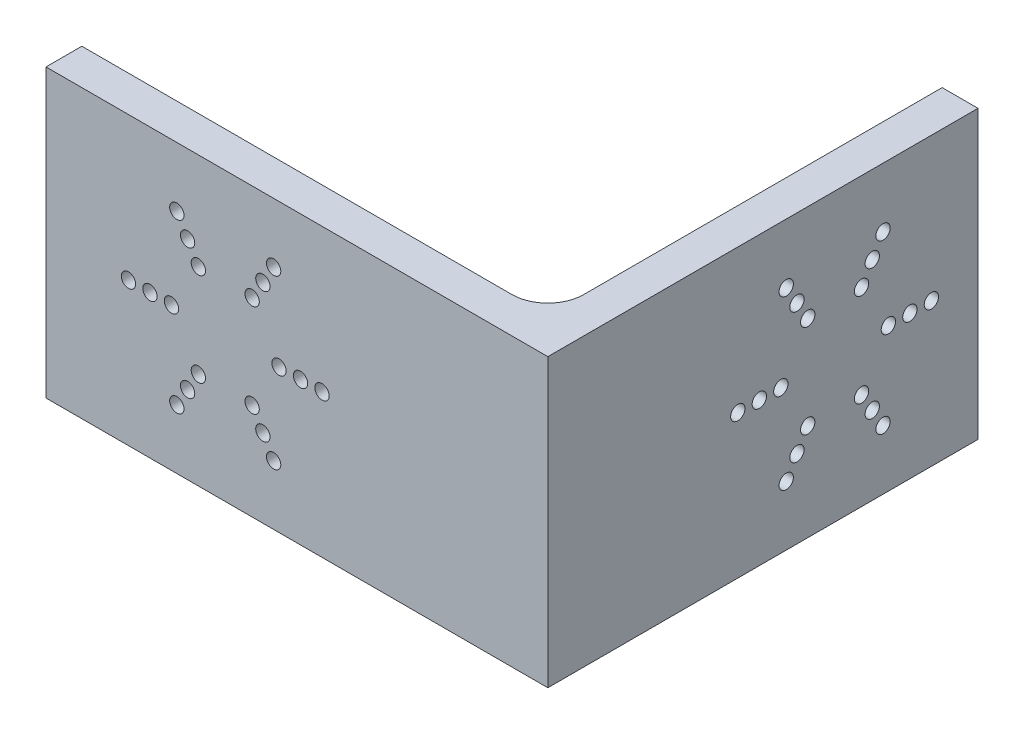
SolidWorks part; units mm, degrees
material "Polylactic Acid"
ref_plane "Top Plane" through (0, 0, 0) normal (0, 0, 1) x (1, 0, 0)
ref_plane "Right Plane" through (0, 0, 0) normal (0, 1, 0) x (1, 0, 0)
ref_plane "Front Plane" through (0, 0, 0) normal (1, 0, 0) x (0, 0, -1)
sketch "Sketch1" plane through (0, 0, 0) normal (0, 1, 0) x (1, 0, 0)
  line L1 (35, -30) -> (-35, -30)
  line L2 (35, -30) -> (35, 30)
  line L3 (35, 30) -> (-35, 30)
  line L4 (-35, -30) -> (-35, 30)
  line L5 (35, -30) -> (-35, 30) construction
  line L6 (35, 30) -> (-35, -30) construction
  point P0 (0, 0)
  dimension "D1" = 70
  dimension "D2" = 60
extrude "Boss-Extrude1" add sketch "Sketch1" along normal mid plane 40
sketch "Sketch2" plane through (0, 20, 0) normal (0, 1, 0) x (1, 0, 0)
  line L0 (-35, -30) -> (35, -30) construction
  line L1 (-35, 30) -> (30, 30)
  line L2 (-35, 30) -> (-35, -25)
  line L3 (-35, -25) -> (30, -25)
  line L4 (30, 30) -> (30, -25)
  line L5 (35, -30) -> (35, 30) construction
  dimension "D1" = 5
  dimension "D2" = 5
extrude "Cut-Extrude1" cut sketch "Sketch2" against normal up to surface (40 mm away) up to face at (0, -20, 0)
fillet "Fillet1" radius 5 1 edges at (30, 0, 25)
sketch "Sketch3" plane through (0, 0, 30) normal (0, 0, 1) x (1, 0, 0)
  line L0 (-2.5, 0) -> (0.5, 0) construction
  line L1 (-6.25, -6.4952) -> (-4.75, -9.0933) construction
  line L11 (-13.75, -6.4952) -> (-15.25, -9.0933) construction
  line L12 (-17.5, 0) -> (-20.5, 0) construction
  line L13 (-13.75, 6.4952) -> (-15.25, 9.0933) construction
  line L14 (-6.25, 6.4952) -> (-4.75, 9.0933) construction
  line L15 (-10, 0) -> (-2.5, 0) construction
  line L19 (-35, 20) -> (-35, -20) construction
  circle A4 centre (-2.5, 0) radius 1
  circle A5 centre (0.5, 0) radius 1
  circle A6 centre (3.5, 0) radius 1
  circle A7 centre (-6.25, -6.4952) radius 1
  circle A8 centre (-4.75, -9.0933) radius 1
  circle A9 centre (-3.25, -11.6913) radius 1
  circle A10 centre (-13.75, -6.4952) radius 1
  circle A11 centre (-15.25, -9.0933) radius 1
  circle A12 centre (-16.75, -11.6913) radius 1
  circle A13 centre (-17.5, 0) radius 1
  circle A14 centre (-20.5, 0) radius 1
  circle A15 centre (-23.5, 0) radius 1
  circle A16 centre (-13.75, 6.4952) radius 1
  circle A17 centre (-15.25, 9.0933) radius 1
  circle A18 centre (-16.75, 11.6913) radius 1
  circle A19 centre (-6.25, 6.4952) radius 1
  circle A20 centre (-4.75, 9.0933) radius 1
  circle A21 centre (-3.25, 11.6913) radius 1
  point P2 (6.0882, 0)
  point P9 (0, 0)
  dimension "D4" = 2
  dimension "D3" = 3
  dimension "D5" = 25
  dimension "D1" = 3
  dimension "D2" = 7.5
extrude "Cut-Extrude2" cut sketch "Sketch3" against normal up to surface (5 mm away) up to face at (-5, 0, 25)
sketch "Sketch4" plane through (35, 0, 0) normal (1, 0, 0) x (0, 0, -1)
  line L0 (17.5, 0) -> (20.5, 0) construction
  line L1 (13.75, -6.4952) -> (15.25, -9.0933) construction
  line L2 (6.25, -6.4952) -> (4.75, -9.0933) construction
  line L3 (2.5, 0) -> (-0.5, 0) construction
  line L4 (6.25, 6.4952) -> (4.75, 9.0933) construction
  line L5 (13.75, 6.4952) -> (15.25, 9.0933) construction
  line L6 (10, 0) -> (17.5, 0) construction
  line L8 (-25, 20) -> (-25, -20) construction
  circle A0 centre (17.5, 0) radius 1
  circle A1 centre (20.5, 0) radius 1
  circle A2 centre (23.5, 0) radius 1
  circle A3 centre (13.75, -6.4952) radius 1
  circle A4 centre (15.25, -9.0933) radius 1
  circle A5 centre (16.75, -11.6913) radius 1
  circle A6 centre (6.25, -6.4952) radius 1
  circle A7 centre (4.75, -9.0933) radius 1
  circle A8 centre (3.25, -11.6913) radius 1
  circle A9 centre (2.5, 0) radius 1
  circle A10 centre (-0.5, 0) radius 1
  circle A11 centre (-3.5, 0) radius 1
  circle A12 centre (6.25, 6.4952) radius 1
  circle A13 centre (4.75, 9.0933) radius 1
  circle A14 centre (3.25, 11.6913) radius 1
  circle A15 centre (13.75, 6.4952) radius 1
  circle A16 centre (15.25, 9.0933) radius 1
  circle A17 centre (16.75, 11.6913) radius 1
  dimension "D3" = 2
  dimension "D2" = 3
  dimension "D5" = 7.5
  dimension "D6" = 21.5
  dimension "D1" = 3
  dimension "D4" = 6
extrude "Cut-Extrude3" cut sketch "Sketch4" against normal up to surface (5 mm away) up to face at (30, 0, -5)
